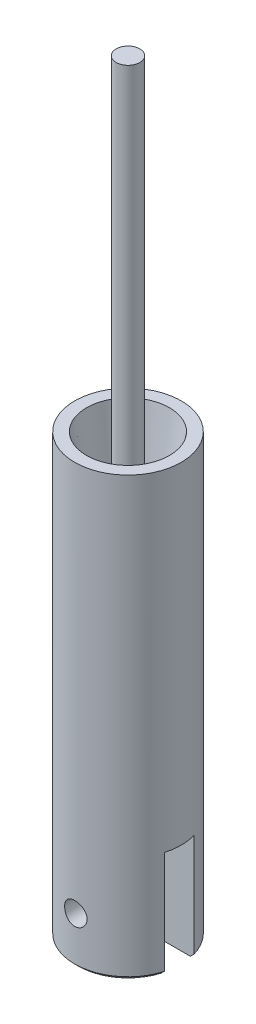
SolidWorks part; units mm, degrees
ref_plane "Płaszczyzna przednia" through (0, 0, 0) normal (0, 0, 1) x (1, 0, 0)
ref_plane "Płaszczyzna górna" through (0, 0, 0) normal (0, 1, 0) x (1, 0, 0)
ref_plane "Płaszczyzna prawa" through (0, 0, 0) normal (1, 0, 0) x (0, 0, -1)
ref_plane "Płaszczyzna1" through (0, 0, 0) normal (0, 0, -1) x (-1, 0, 0)
sketch "Szkic1" plane through (0, 0, 0) normal (0, 0, -1) x (-1, 0, 0)
  line L0 (-4.5, -37) -> (0, -37)
  line L1 (0, -37) -> (0, 0)
  line L2 (0, 0) -> (-4.5, 0)
  line L3 (-4.5, 0) -> (-4.5, -37)
  line L4 (0, -37) -> (0, 0) construction
revolve "Obrót1" add sketch "Szkic1" angle 360 about L4
sketch "Szkic2" plane through (0, -37, 0) normal (0, -1, 0) x (1, 0, 0)
  line L0 (-4.3229, -1.25) -> (4.3229, -1.25)
  arc A0 (4.3229, -1.25) -> (-4.3229, -1.25) centre (0, 0) ccw
extrude "Wytnij-wyciągnięcie1" cut sketch "Szkic2" against normal blind 9
sketch "Szkic3" plane through (0, -28, 0) normal (0, -1, 0) x (1, 0, 0)
  line L0 (4.3229, 1.25) -> (-4.3229, 1.25)
  arc A0 (-4.3229, 1.25) -> (4.3229, 1.25) centre (0, 0) cw
extrude "Dodanie-wyciągnięcie1" add sketch "Szkic3" along normal blind 9
hole_wizard "Otwór1" positions "Szkic5" profile "Szkic4" legacy
sketch "Szkic5" plane through (0, 0, 0) normal (0, 1, 0) x (1, 0, 0)
  point P0 (0, 0)
sketch "Szkic4" plane through (0, 0, 0) normal (1, 0, 0) x (0, 0, 1)
  line L0 (0, 0) -> (0, 6.5)
  line L1 (0, 6.5) -> (2.5, 6.5)
  line L2 (2.5, 6.5) -> (3.5, 0)
  line L3 (3.5, 0) -> (0, 0)
  line L4 (0, 110) -> (0, -10) construction
  dimension "Średnica wewnętrzna" = 5
  dimension "Głębokość" = 6.5
  dimension "Średnica zewnętrzna" = 7
sketch "Szkic6" plane through (0, 0, 0) normal (0, 0, -1) x (-1, 0, 0)
  line L0 (-1, -6.5) -> (0, -6.5)
  line L1 (0, -6.5) -> (0, 27.5)
  line L2 (0, 27.5) -> (-1, 27.5)
  line L3 (-1, 27.5) -> (-1, -6.5)
  line L4 (0, -6.5) -> (0, 27.5) construction
revolve "Obrót2" add sketch "Szkic6" angle 360 about L4
hole_wizard "Otwór Ø1.9 (1.9)1" positions "Szkic8" profile "Szkic7" hole size "Ø1.9" standard "Ansi Metric"
sketch "Szkic8" plane through (0, 0, 1.25) normal (0, 0, -1) x (-1, 0, 0)
  point P0 (0, -33)
sketch "Szkic7" plane through (0, -33, 1.25) normal (1, 0, 0) x (0, 1, 0)
  line L0 (0, 0) -> (0, 3.25)
  line L1 (0, 3.25) -> (0.95, 3.25)
  line L2 (0.95, 3.25) -> (0.95, 0)
  line L5 (0.95, 0) -> (0, 0)
  line L11 (0, -6.35) -> (0, 107.95) construction
  dimension "Średnica otworu na wylot" = 1.9
  dimension "Głębokość otworu na wylot" = 3.25
hole_wizard "Otwór Ø1.9 (1.9)2" positions "Szkic10" profile "Szkic9" hole size "Ø1.9" standard "Ansi Metric"
sketch "Szkic10" plane through (0, 0, -1.25) normal (0, 0, 1) x (1, 0, 0)
  point P0 (0, -33)
sketch "Szkic9" plane through (0, -33, -1.25) normal (1, 0, 0) x (0, -1, 0)
  line L0 (0, 0) -> (0, 3.25)
  line L1 (0, 3.25) -> (0.95, 3.25)
  line L2 (0.95, 3.25) -> (0.95, 0)
  line L5 (0.95, 0) -> (0, 0)
  line L11 (0, -6.35) -> (0, 107.95) construction
  dimension "Średnica otworu na wylot" = 1.9
  dimension "Głębokość otworu na wylot" = 3.25
chamfer "Sfazowanie1" distance 0.3 angle 45 2 edges at (0, -37, 4.5) (0, -37, -4.5)
